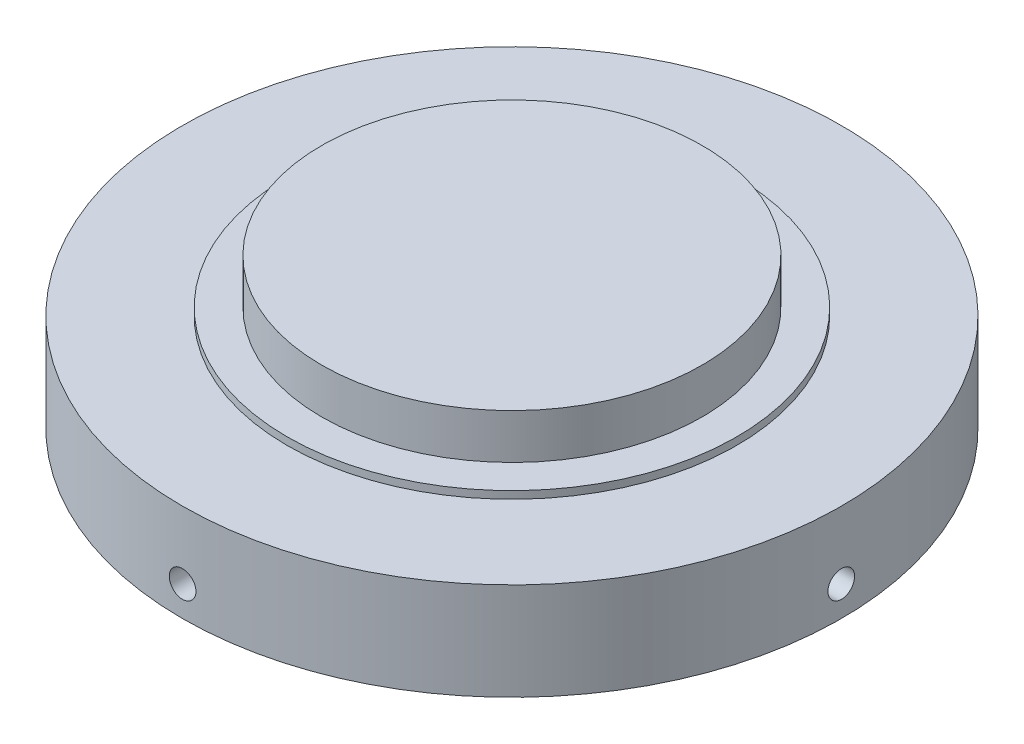
SolidWorks part; units mm, degrees
material "6061 合金"
ref_plane "前视基准面" through (0, 0, 0) normal (0, 0, 1) x (1, 0, 0)
ref_plane "上视基准面" through (0, 0, 0) normal (0, 1, 0) x (1, 0, 0)
ref_plane "右视基准面" through (0, 0, 0) normal (1, 0, 0) x (0, 0, -1)
sketch "草图1" plane through (0, 0, 0) normal (0, 1, 0) x (1, 0, 0)
  circle A0 centre (0, 0) radius 20 construction
sketch "草图2" plane through (0, 0, 0) normal (0, 1, 0) x (1, 0, 0)
  circle A2 centre (0, 0) radius 22
  circle A3 centre (0, 0) radius 22
  dimension "D1" = 2
extrude "凸台-拉伸1" add sketch "草图2" along normal blind 10
sketch "草图3" plane through (0, 0, 0) normal (0, -1, 0) x (1, 0, 0)
  circle A0 centre (0, 0) radius 20 construction
  circle A1 centre (0, 0) radius 20
extrude "切除-拉伸1" cut sketch "草图3" against normal blind 4
sketch "草图4" plane through (0, 10, 0) normal (0, 1, 0) x (1, 0, 0)
  circle A0 centre (0, 0) radius 12.7
  circle A1 centre (0, 0) radius 22 construction
  circle A2 centre (0, 0) radius 22
extrude "切除-拉伸2" cut sketch "草图4" against normal blind 3
ref_plane "基准面1" through (0, 0, -22) normal (0, 0, -1) x (-1, 0, 0)
sketch "草图5" plane through (0, 0, -22) normal (0, 0, -1) x (-1, 0, 0)
  line L0 (0, 0) -> (0, 2) construction
  line L1 (0, 5.5) -> (0, -5.5) construction
  dimension "D1" = 2
sketch "草图9" plane through (0, 0, 0) normal (0, -1, 0) x (1, 0, 0)
  circle A4 centre (0, 0) radius 20.15
  circle A5 centre (0, 0) radius 20.15
  dimension "D1" = 0.15
extrude "切除-拉伸3" cut sketch "草图9" against normal up to surface (4 mm away) up to face at (0, 4, -20)
sketch "草图10" plane through (0, 7, 0) normal (0, 1, 0) x (1, 0, 0)
  circle A0 centre (0, 0) radius 15
  circle A1 centre (0, 0) radius 22 construction
  circle A2 centre (0, 0) radius 22
  dimension "D1" = 30
extrude "切除-拉伸4" cut sketch "草图10" against normal blind 0.5
hole_wizard "#2-56 螺纹孔1" positions "3D草图2" profile "草图7" tap size "#2-56" standard "ANSI Inch"
sketch3d "3D草图2"
  point P0 (0, 2, -22)
  point P5 (0, 2, -22)
cosmetic thread "孔螺蚊线9" parameters "D1"=1.89, "D2"=2.1844
sketch "草图7" plane through (0, 2, -22) normal (1, 0, 0) x (0, 1, 0)
  line L0 (0, 0) -> (0, 5.5342)
  line L1 (0, 5.5342) -> (0.889, 5)
  line L2 (0.889, 5) -> (0.889, 0)
  line L5 (0.889, 0) -> (0, 0)
  line L10 (0, 5.5342) -> (-0.889, 5) construction
  line L11 (0, -6.35) -> (0, 107.95) construction
  dimension "螺纹孔钻头直径" = 1.778
  dimension "螺纹孔钻头深度" = 5
  dimension "导头角度" = 118
ref_plane "基准面2" [suppressed] through (22, 0, 0) normal (1, 0, 0) x (0, 0, -1)
sketch "草图11" [suppressed] plane through (22, 0, 0) normal (1, 0, 0) x (0, 0, -1)
  line L0 (0, 0) -> (0, 2.1408) construction
  line L1 (0, 16.5) -> (0, -16.5) construction
  circle A0 centre (0, 2.1408) radius 0.475
pattern_circular "阵列(圆周)1" count 4 over 360 about axis through (0, 0, 0) along (0, 1, 0) of "#2-56 螺纹孔1"
cosmetic thread "孔螺蚊线11" parameters "D1"=1.8696, "D2"=2.1844
cosmetic thread "孔螺蚊线12" parameters "D1"=1.8696, "D2"=2.1844
cosmetic thread "孔螺蚊线13" parameters "D1"=1.8696, "D2"=2.1844
